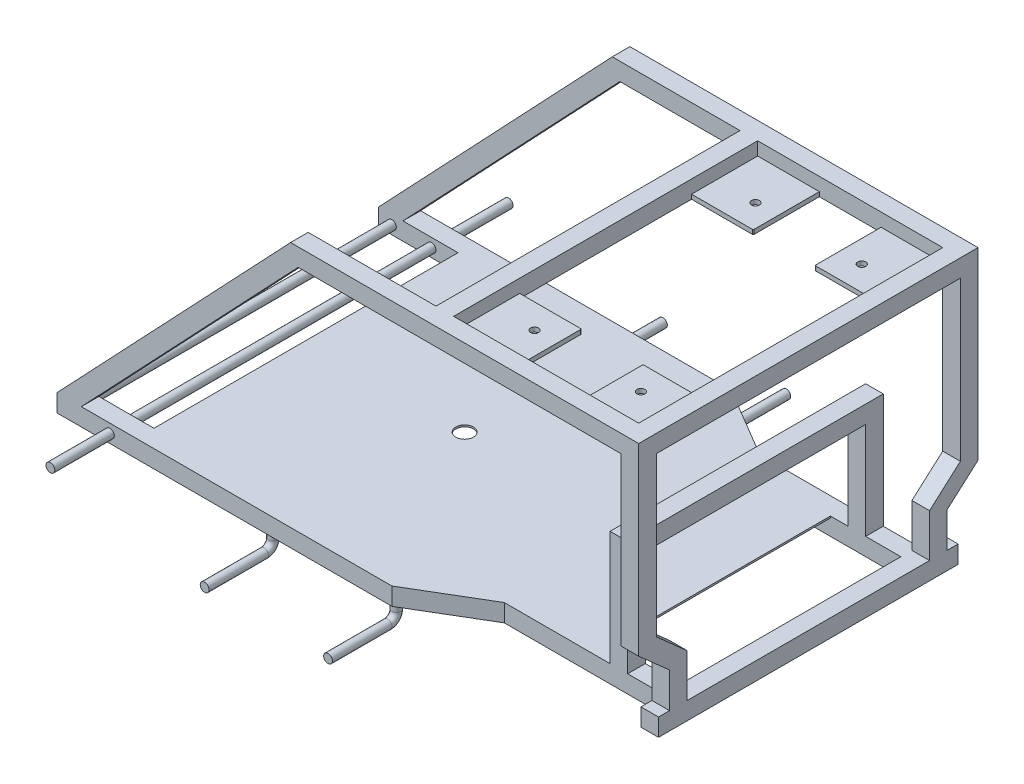
SolidWorks part; units mm, degrees
ref_plane "Front Plane" through (0, 0, 0) normal (0, 0, 1) x (1, 0, 0)
ref_plane "Top Plane" through (0, 0, 0) normal (0, 1, 0) x (1, 0, 0)
ref_plane "Right Plane" through (0, 0, 0) normal (1, 0, 0) x (0, 0, -1)
sketch "Sketch1" plane through (0, 0, 0) normal (0, 1, 0) x (1, 0, 0)
  line L0 (450.4334, 0) -> (-450.4334, 0) construction
  line L1 (0, 292.4073) -> (0, -292.4073) construction
  line L2 (-330, -192.5) -> (-330, 192.5) construction
  line L3 (330, 145) -> (330, -145) construction
  line L4 (-330, 192.5) -> (50, 192.5)
  line L5 (50, 192.5) -> (130, 145)
  line L6 (130, 145) -> (330, 145)
  line L7 (-330, 172.5) -> (44.5099, 172.5)
  line L8 (44.5099, 172.5) -> (124.5099, 125)
  line L9 (124.5099, 125) -> (310, 125)
  line L10 (-330, 192.5) -> (-330, 172.5)
  line L11 (330, 145) -> (330, 125)
  line L12 (130, -145) -> (330, -145)
  line L13 (50, -192.5) -> (130, -145)
  line L14 (-330, -192.5) -> (50, -192.5)
  line L15 (-330, -192.5) -> (-330, -172.5)
  line L16 (-330, -172.5) -> (44.5099, -172.5)
  line L17 (44.5099, -172.5) -> (124.5099, -125)
  line L18 (124.5099, -125) -> (310, -125)
  line L19 (330, -145) -> (330, -125)
  line L20 (124.5099, 125) -> (330, 125) construction
  line L22 (310, 125) -> (310, -125)
  line L24 (330, 125) -> (330, -125)
  point P4 (0, 0)
  point P8 (0, 0)
  point P10 (-330, 0)
  point P13 (330, 0)
  dimension "D1" = 330
  dimension "D2" = 385
  dimension "D3" = 290
  dimension "D4" = 330
  dimension "D5" = 380
  dimension "D6" = 200
  dimension "D7" = 20
  dimension "D8" = 20
  dimension "D9" = 20
extrude "Boss-Extrude1" add sketch "Sketch1" along normal mid plane 20
sketch "Sketch2" plane through (0, 0, 0) normal (0, 0, 1) x (1, 0, 0)
  line L0 (0, 0) -> (-330, 0) construction
  line L1 (-330, 10) -> (-330, -10) construction
  line L2 (-330, -10) -> (50, -10) construction
  line L3 (-240, 10) -> (-220, 10)
  line L4 (-240, 10) -> (-240, -10)
  line L5 (-240, -10) -> (-220, -10)
  line L6 (-220, 10) -> (-220, -10)
  line L7 (-240, 10) -> (-220, -10) construction
  line L8 (-240, -10) -> (-220, 10) construction
  line L9 (-270, 3.4817) -> (-270, -3.4817) construction
  line L10 (0, 0) -> (330, 0) construction
  line L11 (330, 10) -> (330, -10) construction
  line L13 (155, 10) -> (175, 10)
  line L14 (155, 10) -> (155, -10)
  line L15 (155, -10) -> (175, -10)
  line L16 (175, 10) -> (175, -10)
  line L17 (155, 10) -> (175, -10) construction
  line L18 (155, -10) -> (175, 10) construction
  circle A0 centre (-315, 0) radius 5
  point P8 (-230, 0)
  point P17 (-270, 0)
  point P20 (165, 0)
  dimension "D2" = 10
  dimension "D1" = 315
  dimension "D3" = 45
  dimension "D4" = 40
  dimension "D5" = 20
  dimension "D6" = 20
  dimension "D7" = 20
extrude "Boss-Extrude2" add sketch "Sketch2" along normal mid plane 350
sketch "Sketch3" plane through (0, 0, 0) normal (0, 0, 1) x (1, 0, 0)
  line L0 (0, 0) -> (-315, 0) construction
  circle A0 centre (-270, 0) radius 5
  dimension "D3" = 10
  dimension "D1" = 315
  dimension "D2" = 45
extrude "Boss-Extrude3" add sketch "Sketch3" along normal mid plane 520
sketch "Sketch4" plane through (0, -10, 0) normal (0, -1, 0) x (1, 0, 0)
  line L0 (-270, 260) -> (-270, -260) construction
  line L1 (-265, 260) -> (-275, 260) construction
  line L2 (-275, -260) -> (-265, -260) construction
  line L3 (-330, 182.5) -> (50.8979, 182.5) construction
  line L4 (-330, 172.5) -> (-330, 192.5) construction
  circle A0 centre (-95, 182.5) radius 5
  circle A1 centre (45, 182.5) radius 5
  dimension "D1" = 10
  dimension "D2" = 10
  dimension "D3" = 175
  dimension "D4" = 140
sketch3d "3DSketch1"
  line L0 (-95, -10, 182.5) -> (-95, -20, 182.5)
  line L1 (-95, -30, 192.5) -> (-95, -30, 260)
  line L2 (45, -10, 182.5) -> (45, -20, 182.5)
  line L3 (45, -30, 192.5) -> (45, -30, 260)
  arc A0 (45, -20, 182.5) -> (45, -30, 192.5) centre (45, -20, 192.5) ccw
  arc A1 (-95, -20, 182.5) -> (-95, -30, 192.5) centre (-95, -20, 192.5) ccw
  point P10 (45, -30, 182.5)
  point P11 (35, -20, 192.5)
  point P14 (-95, -30, 182.5)
  point P15 (-105, -20, 192.5)
  dimension "D5" = 10
  dimension "D1" = 77.5
  dimension "D2" = 77.5
  dimension "D3" = 20
  dimension "D4" = 20
sweep "Sweep1" add profiles "Sketch4" path "3DSketch1"
mirror "Mirror1" about plane through (0, 0, 0) normal (0, 0, 1) of "Sweep1"
sketch "Sketch5" plane through (175, 0, 0) normal (1, 0, 0) x (0, 0, -1)
  line L1 (-175, 10) -> (-145, 10)
  line L2 (-175, 10) -> (-175, -10)
  line L3 (-175, -10) -> (-145, -10)
  line L4 (-145, 10) -> (-145, -10)
  line L5 (145, 10) -> (175, 10)
  line L6 (145, 10) -> (145, -10)
  line L7 (145, -10) -> (175, -10)
  line L8 (175, 10) -> (175, -10)
extrude "Cut-Extrude1" cut sketch "Sketch5" against normal up to surface (20 mm away) up to face at (155, 0, 160)
sketch "Sketch6" plane through (0, 10, 0) normal (0, 1, 0) x (1, 0, 0)
  line L0 (-220, -172.5) -> (-220, 172.5) construction
  line L1 (44.5099, -172.5) -> (-220, -172.5) construction
  line L2 (124.5099, -125) -> (44.5099, -172.5) construction
  line L3 (155, -125) -> (124.5099, -125) construction
  line L4 (155, -125) -> (155, 125) construction
  line L5 (124.5099, 125) -> (155, 125) construction
  line L6 (44.5099, 172.5) -> (124.5099, 125) construction
  line L7 (-220, 172.5) -> (44.5099, 172.5) construction
  line L8 (-220, -172.5) -> (-220, 172.5)
  line L9 (44.5099, -172.5) -> (-220, -172.5)
  line L10 (124.5099, -125) -> (44.5099, -172.5)
  line L11 (155, -125) -> (124.5099, -125)
  line L12 (155, -125) -> (155, 125)
  line L13 (124.5099, 125) -> (155, 125)
  line L14 (44.5099, 172.5) -> (124.5099, 125)
  line L15 (-220, 172.5) -> (44.5099, 172.5)
  line L16 (310, -125) -> (175, -125) construction
  line L17 (175, 125) -> (230, 125)
  line L18 (175, 125) -> (175, -125)
  line L19 (175, -125) -> (230, -125)
  line L20 (230, 125) -> (230, -125)
  dimension "D1" = 55
extrude "Boss-Extrude4" add sketch "Sketch6" against normal blind 2
sketch "Sketch7" plane through (0, 10, 0) normal (0, 1, 0) x (1, 0, 0)
  line L0 (0, 0) -> (-320, 0) construction
  line L1 (-320, 172.5) -> (-320, -172.5) construction
  circle A0 centre (-60, 0) radius 10
  dimension "D1" = 20
  dimension "D2" = 260
extrude "Cut-Extrude2" cut sketch "Sketch7" against normal blind 30
sketch "Sketch8" plane through (0, 0, 0) normal (0, 0, 1) x (1, 0, 0)
  line L0 (250, 140) -> (250, -10) construction
  line L2 (330, 10) -> (330, -10) construction
  line L3 (130, -10) -> (330, -10) construction
  line L9 (250, 140) -> (270, 140)
  line L10 (250, 140) -> (250, -10)
  line L11 (250, -10) -> (270, -10)
  line L12 (270, 140) -> (270, -10)
  dimension "D1" = 80
  dimension "D2" = 150
  dimension "D3" = 20
extrude "Boss-Extrude5" add sketch "Sketch8" along normal mid plane 290
sketch "Sketch9" plane through (270, 0, 0) normal (1, 0, 0) x (0, 0, -1)
  line L1 (-125, -10) -> (125, -10)
  line L2 (-125, -10) -> (-125, 120)
  line L3 (-125, 120) -> (125, 120)
  line L4 (125, -10) -> (125, 120)
  line L5 (-145, 140) -> (145, 140) construction
  dimension "D1" = 20
extrude "Cut-Extrude3" cut sketch "Sketch9" against normal up to surface (20 mm away) up to face at (250, 37.5, 0)
sketch "Sketch10" plane through (330, 0, 0) normal (1, 0, 0) x (0, 0, -1)
  line L0 (-157.5, 10) -> (-157.5, 50)
  line L1 (145, -10) -> (170, -10)
  line L2 (-157.5, 50) -> (-192.5, 80.9967)
  line L3 (-192.5, 80.9967) -> (-192.5, 290)
  line L4 (-192.5, 290) -> (0, 290)
  line L5 (-172.5, 270) -> (-172.5, 90)
  line L6 (-172.5, 90) -> (-137.5, 59.0033)
  line L7 (-137.5, 59.0033) -> (-137.5, 10)
  line L8 (172.5, 270) -> (172.5, 90)
  line L9 (170, 10) -> (170, -10)
  line L10 (0, 0) -> (0, 270) construction
  line L11 (172.5, 90) -> (137.5, 59.0033)
  line L12 (145, 10) -> (170, 10)
  line L13 (145, 10) -> (145, -10)
  line L14 (-157.5, 10) -> (-137.5, 10)
  line L15 (-145, -10) -> (145, -10) construction
  line L16 (137.5, 59.0033) -> (137.5, 10)
  line L17 (-192.5, 290) -> (192.5, 290)
  line L18 (-192.5, 290) -> (-192.5, 80.9967)
  line L19 (-172.5, 270) -> (172.5, 270)
  line L21 (157.5, 10) -> (137.5, 10)
  line L22 (157.5, 10) -> (157.5, 50)
  line L23 (157.5, 50) -> (192.5, 80.9967)
  line L24 (192.5, 80.9967) -> (192.5, 290)
  line L35 (-145, 10) -> (-125, 10) construction
  line L37 (-145, 10) -> (-170, 10)
  line L38 (-145, 10) -> (-145, -10)
  line L39 (-145, -10) -> (-170, -10)
  line L40 (-170, 10) -> (-170, -10)
  line M16 (145, 10) -> (-145, 10)
  dimension "D1" = 55
  dimension "D2" = 20
  dimension "D3" = 300
  dimension "D4" = 20
  dimension "D5" = 80
  dimension "D6" = 40
  dimension "D7" = 20
  dimension "D8" = 385
  dimension "D9" = 20
  dimension "D10" = 20
  dimension "D11" = 25
extrude "Boss-Extrude6" add sketch "Sketch10" against normal blind 20 contours L23 L24 L17 L4 L3 L2 L0 L7 L6 L5 L19 L8 L11 L16 L22 M16 | L38 L37 L40 L39 | L1 L9 L12 L13
sketch "Sketch13" plane through (0, 0, -192.5) normal (0, 0, -1) x (-1, 0, 0)
  line L0 (-310, 290) -> (65, 290)
  line L1 (65, 290) -> (330, 10)
  line L2 (-330, 80.9967) -> (-330, 290) construction
  line L3 (-310, 270) -> (56.3915, 270)
  line L4 (56.3915, 270) -> (302.4629, 10)
  line L5 (330, 10) -> (302.4629, 10)
  line L7 (56.3915, 270) -> (315.4741, -3.7477) construction
  line L8 (-310, 270) -> (-310, 290)
  dimension "D1" = 395
  dimension "D2" = 20
extrude "Boss-Extrude7" add sketch "Sketch13" against normal blind 20
mirror "Mirror2" about plane through (0, 0, 0) normal (0, 0, 1) of "Boss-Extrude7"
sketch "Sketch14" plane through (0, 0, 0) normal (0, 0, 1) x (1, 0, 0)
  line L0 (-65, 290) -> (330, 290) construction
  line L5 (80, 290) -> (100, 290)
  line L6 (80, 290) -> (80, 270)
  line L7 (80, 270) -> (100, 270)
  line L8 (100, 290) -> (100, 270)
  line L9 (310, 270) -> (-56.3915, 270) construction
  dimension "D1" = 20
  dimension "D2" = 165
extrude "Boss-Extrude8" add sketch "Sketch14" along normal mid plane 350
ref_plane "Plane1" through (0, 270, 0) normal (0, -1, 0) x (-1, 0, 0)
sketch "Sketch15" plane through (0, 270, 0) normal (0, -1, 0) x (-1, 0, 0)
  line L0 (0, 0) -> (-408.027, 0) construction
  line L1 (-205, 172.5) -> (-205, -172.5) construction
  line L2 (-100, 172.5) -> (-310, 172.5) construction
  line L3 (-100, -172.5) -> (-310, -172.5) construction
  line L4 (-310, 97.5) -> (-241, 97.5)
  line L5 (-100, 172.5) -> (-170, 172.5)
  line L6 (-100, 172.5) -> (-100, 97.5)
  line L7 (-100, 97.5) -> (-169, 97.5)
  line L8 (-170, 172.5) -> (-170, 98.5)
  line L9 (-240, 172.5) -> (-240, 98.5)
  line L10 (-310, 172.5) -> (-240, 172.5)
  line L11 (-310, 172.5) -> (-310, 97.5)
  line L12 (-310, -172.5) -> (-310, -97.5)
  line L13 (-310, -172.5) -> (-240, -172.5)
  line L14 (-240, -172.5) -> (-240, -98.5)
  line L15 (-310, -97.5) -> (-241, -97.5)
  line L16 (-100, -97.5) -> (-169, -97.5)
  line L17 (-170, -172.5) -> (-170, -98.5)
  line L18 (-100, -172.5) -> (-170, -172.5)
  line L19 (-100, -172.5) -> (-100, -97.5)
  line L20 (-100, 172.5) -> (-170, 98.5) construction
  arc A0 (-169, 97.5) -> (-170, 98.5) centre (-169, 98.5) cw
  arc A1 (-241, 97.5) -> (-240, 98.5) centre (-241, 98.5) ccw
  arc A2 (-241, -97.5) -> (-240, -98.5) centre (-241, -98.5) cw
  arc A3 (-169, -97.5) -> (-170, -98.5) centre (-169, -98.5) ccw
  circle A4 centre (-144.668, 125.2796) radius 4.5
  circle A5 centre (-265.332, 125.2796) radius 4.5
  circle A6 centre (-265.332, -125.2796) radius 4.5
  circle A7 centre (-144.668, -125.2796) radius 4.5
  point P16 (-170, 97.5)
  dimension "D3" = 1
  dimension "D4" = 9
  dimension "D1" = 75
  dimension "D2" = 70
  dimension "D5" = 65
extrude "Boss-Extrude9" add sketch "Sketch15" against normal blind 5
sketch "Sketch16" plane through (0, -10, 0) normal (0, -1, 0) x (1, 0, 0)
  line L0 (330, 0) -> (-320, 0) construction
  line L1 (330, 170) -> (330, -170) construction
  line L2 (-320, 172.5) -> (-320, -172.5) construction
  line L3 (5, 192.5) -> (5, -192.5) construction
  line L4 (50, -192.5) -> (-330, -192.5) construction
  point P6 (5, 0)
  point P13 (5, 0)
